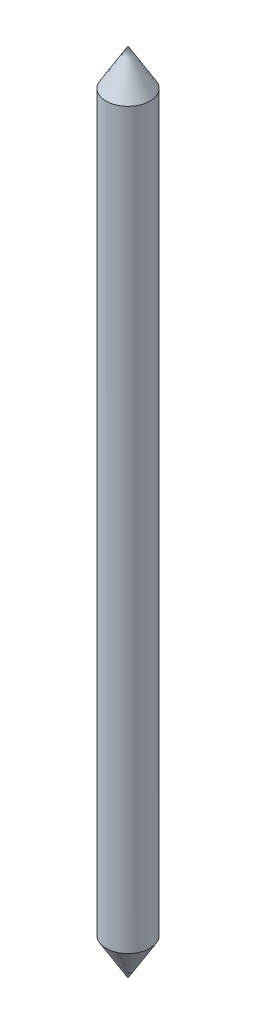
SolidWorks part; units mm, degrees
ref_plane "Front Plane" through (0, 0, 0) normal (0, 0, 1) x (1, 0, 0)
ref_plane "Top Plane" through (0, 0, 0) normal (0, 1, 0) x (1, 0, 0)
ref_plane "Right Plane" through (0, 0, 0) normal (1, 0, 0) x (0, 0, -1)
sketch "Sketch1" plane through (0, 0, 0) normal (1, 0, 0) x (0, 0, -1)
  line L0 (0, -139.7) -> (0, 139.7)
  line L1 (0, 139.7) -> (7.62, 127)
  line L2 (7.62, 127) -> (7.62, -127)
  line L3 (7.62, -127) -> (0, -139.7)
  point P2 (0, 0)
  point P5 (7.62, 0)
  dimension "D1" = 279.4
  dimension "D2" = 12.7
  dimension "D3" = 7.62
revolve "Revolve1" add sketch "Sketch1" angle 360 about L0
